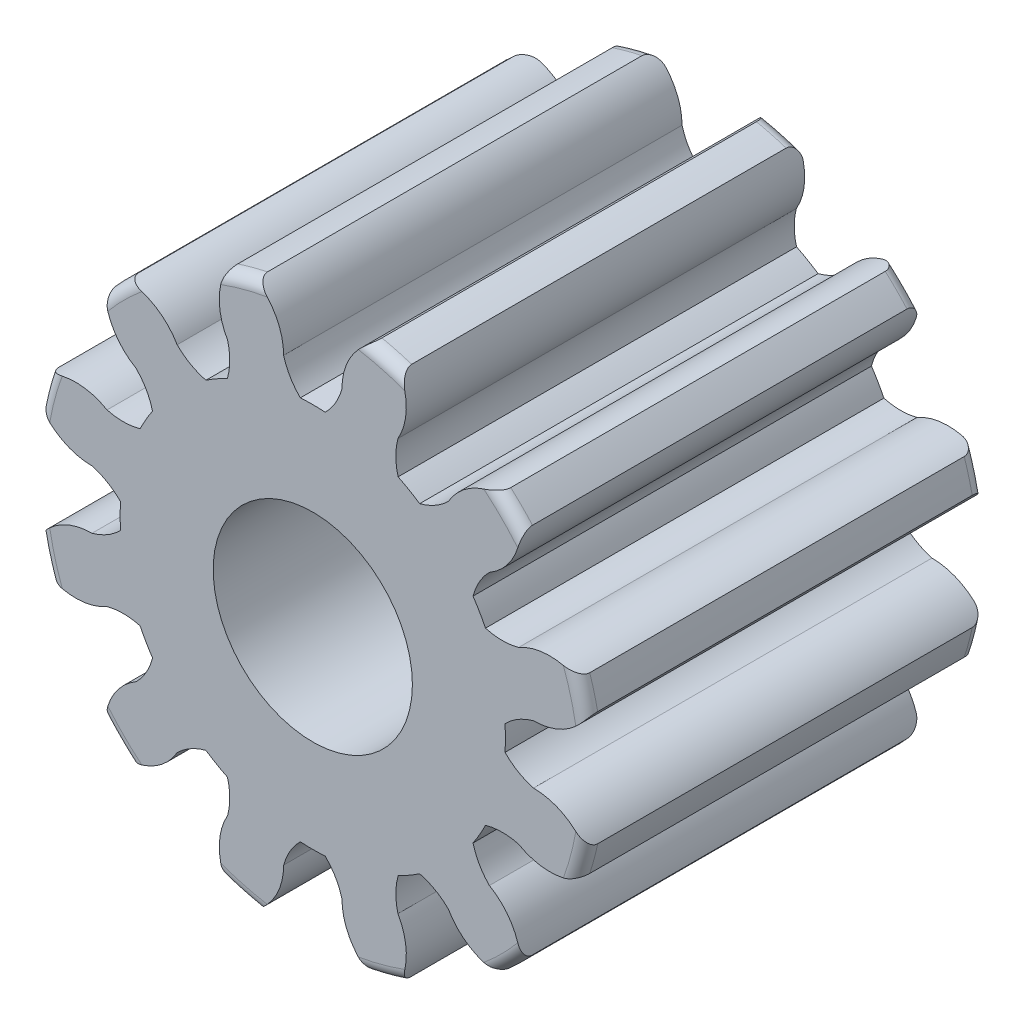
SolidWorks part; units mm, degrees
ref_plane "Alzado" through (0, 0, 0) normal (0, 0, 1) x (1, 0, 0)
ref_plane "Planta" through (0, 0, 0) normal (0, 1, 0) x (1, 0, 0)
ref_plane "Vista lateral" through (0, 0, 0) normal (1, 0, 0) x (0, 0, -1)
sketch "Croquis1" plane through (0, 0, 0) normal (0, 0, 1) x (1, 0, 0)
  circle A0 centre (0, 0) radius 7
  circle A1 centre (0, 0) radius 2.5
  dimension "D1" = 14
  dimension "D2" = 5
extrude "Saliente-Extruir1" add sketch "Croquis1" along normal blind 10
sketch "Croquis2" plane through (0, 0, 10) normal (0, 0, 1) x (1, 0, 0)
  arc A0 (-0.7319, 5.5406) -> (-0.3127, 4.8249) centre (0.785, 5.9484) ccw
  arc A1 (0.3121, 4.8249) -> (-0.3127, 4.8249) centre (0, 0) ccw
  arc A2 (-1.8974, 7.0581) -> (1.8965, 7.0584) centre (-0.0004, 5.851) cw
  arc A6 (-0.7319, 5.5406) -> (-1.8974, 7.0581) centre (-2.3027, 5.5405) ccw
  arc A8 (1.8965, 7.0584) -> (0.7312, 5.5407) centre (2.302, 5.5408) ccw
  arc A9 (0.3121, 4.8249) -> (0.7312, 5.5407) centre (-0.7858, 5.9483) ccw
fillet "Redondeo1" radius 0.3 2 edges at (7, 0, 0) (7, 0, 10)
extrude "Cortar-Extruir1" cut sketch "Croquis2" against normal up to next
pattern_circular "MatrizC1" count 12 over 360 about axis through (0, 0, 0) along (0, 0, 1) of "Cortar-Extruir1"
